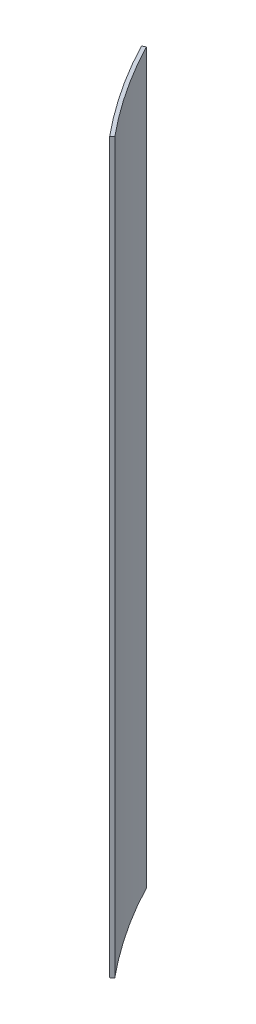
SolidWorks part; units mm, degrees
ref_plane "前视基准面" through (0, 0, 0) normal (0, 0, 1) x (1, 0, 0)
ref_plane "上视基准面" through (0, 0, 0) normal (0, 1, 0) x (1, 0, 0)
ref_plane "右视基准面" through (0, 0, 0) normal (1, 0, 0) x (0, 0, -1)
sketch "草图1" plane through (0, 0, 0) normal (0, 1, 0) x (1, 0, 0)
  line L0 (0, 0) -> (-1316.976, -686.1481) construction
  line L1 (0, 0) -> (-1145.5387, -944.9688) construction
  line L2 (-1145.5387, -944.9688) -> (-1137.8246, -938.6054)
  line L3 (-1316.976, -686.1481) -> (-1308.1075, -681.5276)
  circle A0 centre (0, 0) radius 1475 construction
  circle A1 centre (0, 0) radius 1485 construction
  arc A2 (-1137.8246, -938.6054) -> (-1308.1075, -681.5276) centre (0, 0) cw
  arc A3 (-1145.5387, -944.9688) -> (-1316.976, -686.1481) centre (0, 0) cw
  dimension "D1" = 2950
  dimension "D2" = 2970
  dimension "D3" = 12
extrude "凸台-拉伸3" add sketch "草图1" along normal blind 2000
sketch "草图2" plane through (0, 0, 0) normal (0, 1, 0) x (1, 0, 0)
  line L0 (0, 0) -> (-1316.976, -686.1481) construction
  line L1 (0, 0) -> (-1304.8005, -709.028) construction
  line L2 (0, 0) -> (-1308.495, -702.1864) construction
  line L3 (-1301.0701, -715.8502) -> (0, 0) construction
  line L4 (-1303.2082, -699.3493) -> (-1304.9705, -700.295)
  line L5 (-1297.5656, -713.922) -> (-1295.8133, -712.9579)
  circle A0 centre (0, 0) radius 1475 construction
  circle A1 centre (0, 0) radius 1485 construction
  circle A2 centre (0, 0) radius 1480 construction
  circle A3 centre (0, 0) radius 1481 construction
  circle A4 centre (0, 0) radius 1479 construction
  arc A5 (-1304.9705, -700.295) -> (-1297.5656, -713.922) centre (0, 0) ccw
  arc A6 (-1303.2082, -699.3493) -> (-1295.8133, -712.9579) centre (0, 0) ccw
  dimension "D1" = 1
  dimension "D2" = 0.3
  dimension "D3" = 0.3
extrude "切除-拉伸1" cut sketch "草图2" along normal blind 30
